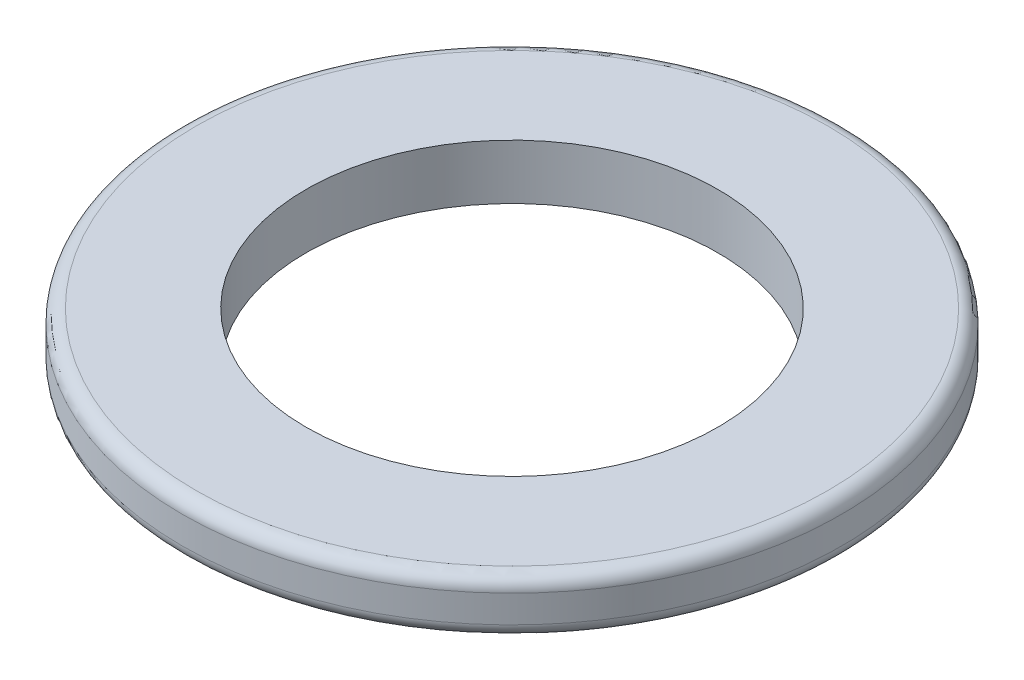
SolidWorks part; units mm, degrees
ref_plane "Front Plane" through (0, 0, 0) normal (0, 0, 1) x (1, 0, 0)
ref_plane "Top Plane" through (0, 0, 0) normal (0, 1, 0) x (1, 0, 0)
ref_plane "Right Plane" through (0, 0, 0) normal (1, 0, 0) x (0, 0, -1)
sketch "Sketch1" plane through (0, 0, 0) normal (0, 1, 0) x (1, 0, 0)
  circle A0 centre (0, 0) radius 2.4
  circle A1 centre (0, 0) radius 1.5
  dimension "D1" = 3
  dimension "D2" = 4.8
extrude "Boss-Extrude1" add sketch "Sketch1" along normal blind 0.4
fillet "Fillet1" radius 0.1 2 edges at (0, 0.4, 2.4) (0, 0, 2.4)
